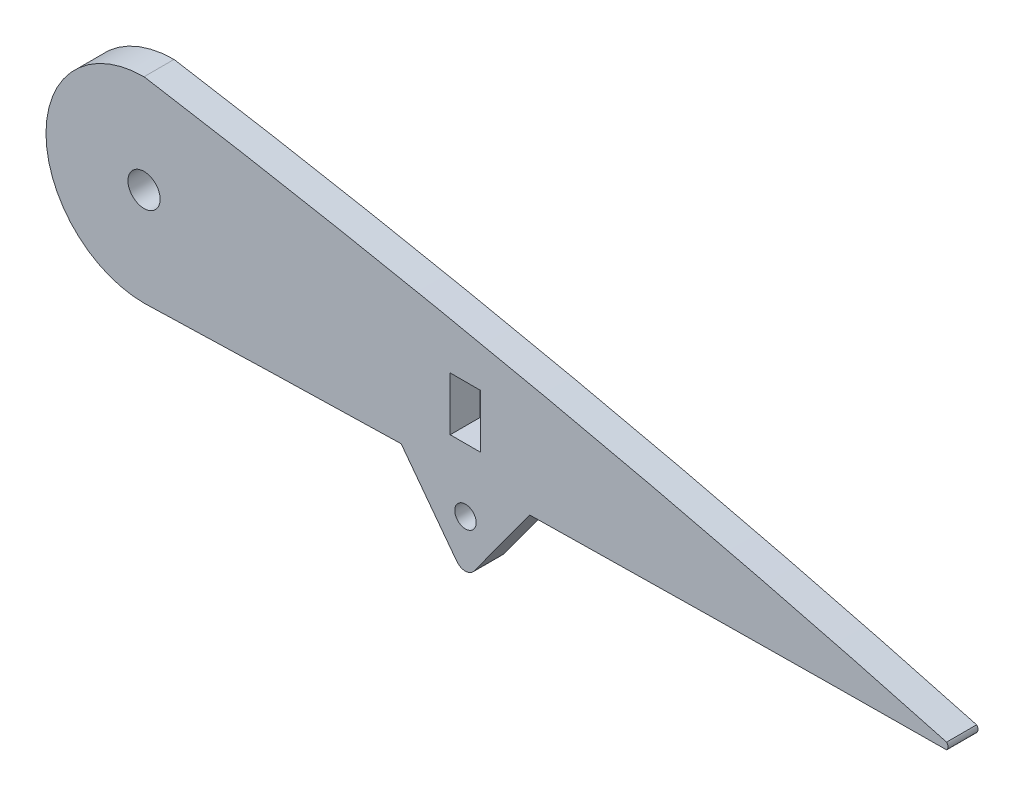
SolidWorks part; units mm, degrees
material "Фанера"
ref_plane "Front Plane" through (0, 0, 0) normal (0, 0, 1) x (1, 0, 0)
ref_plane "Top Plane" through (0, 0, 0) normal (0, 1, 0) x (1, 0, 0)
ref_plane "Right Plane" through (0, 0, 0) normal (1, 0, 0) x (0, 0, -1)
curve "Кривая5"
  spline degree 3 poles (0.048, 0.6214, 0) (0.0227, 0.3735, 0) (-0.0278, -0.1225, 0) (0.078, -0.8844, 0) (0.3497, -1.6388, 0) (0.8143, -2.3651, 0) (1.4635, -3.0393, 0) (2.291, -3.661, 0) (3.3059, -4.2358, 0) (4.5353, -4.7737, 0) (6.0297, -5.2822, 0) (7.869, -5.7653, 0) (10.1688, -6.2217, 0) (13.0754, -6.6396, 0) (16.7281, -6.993, 0) (21.19, -7.2473, 0) (26.4, -7.3766, 0) (32.1974, -7.3763, 0) (38.3978, -7.2614, 0) (44.8576, -7.0566, 0) (51.4865, -6.7865, 0) (58.231, -6.4723, 0) (65.0521, -6.1329, 0) (71.9108, -5.784, 0) (78.7714, -5.4397, 0) (85.6105, -5.111, 0) (92.4321, -4.805, 0) (99.255, -4.532, 0) (106.0974, -4.2783, 0) (112.9692, -4.0031, 0) (119.8644, -3.7232, 0) (126.7739, -3.4401, 0) (133.6816, -3.1587, 0) (140.5819, -2.8824, 0) (147.472, -2.6139, 0) (154.3526, -2.3556, 0) (161.225, -2.1094, 0) (168.0909, -1.8766, 0) (174.9516, -1.6586, 0) (181.8086, -1.4564, 0) (188.6632, -1.2704, 0) (195.5166, -1.1011, 0) (202.3695, -0.9486, 0) (209.2212, -0.8129, 0) (216.0668, -0.6936, 0) (222.8864, -0.5903, 0) (229.6176, -0.5029, 0) (236.0874, -0.4315, 0) (241.9808, -0.3765, 0) (246.559, -0.3395, 0) (249.1205, -0.3213, 0) (250, -0.315, 0) knots 0 0 0 0 0.002941 0.005884 0.009016 0.012365 0.016008 0.020037 0.024574 0.029784 0.035897 0.04324 0.052276 0.063635 0.077983 0.095698 0.11652 0.139661 0.164312 0.189919 0.216157 0.242838 0.269834 0.296993 0.324123 0.351139 0.378036 0.404946 0.431961 0.459078 0.486347 0.513641 0.540929 0.568176 0.59538 0.622543 0.649673 0.676775 0.703855 0.730919 0.757971 0.785018 0.812062 0.839103 0.866132 0.893099 0.919831 0.94581 0.969681 0.98959 1 1 1 1
curve "Кривая6"
  spline degree 3 poles (250, 0.315, 0) (249.1557, 0.545, 0) (246.7202, 1.2085, 0) (242.3913, 2.3583, 0) (236.8498, 3.7876, 0) (230.7799, 5.298, 0) (224.4559, 6.8129, 0) (218.0305, 8.2916, 0) (211.5624, 9.7197, 0) (205.0724, 11.0924, 0) (198.568, 12.4079, 0) (192.0524, 13.6653, 0) (185.5276, 14.8641, 0) (178.9953, 16.0034, 0) (172.4571, 17.0824, 0) (165.9143, 18.0998, 0) (159.3687, 19.0545, 0) (152.8218, 19.9449, 0) (146.2754, 20.7693, 0) (139.7314, 21.5257, 0) (133.1918, 22.212, 0) (126.6587, 22.8257, 0) (120.1368, 23.364, 0) (113.6286, 23.8247, 0) (107.1527, 24.2002, 0) (100.7411, 24.4984, 0) (94.4118, 24.6866, 0) (88.1559, 24.7401, 0) (81.949, 24.6588, 0) (75.7805, 24.441, 0) (69.6537, 24.0819, 0) (63.5754, 23.578, 0) (57.5552, 22.9249, 0) (51.6058, 22.1191, 0) (45.7444, 21.1566, 0) (39.9959, 20.0354, 0) (34.3979, 18.7563, 0) (29.0104, 17.3276, 0) (23.9258, 15.7719, 0) (19.2707, 14.1343, 0) (15.1791, 12.4833, 0) (11.7405, 10.8956, 0) (8.9594, 9.4296, 0) (6.7609, 8.1086, 0) (5.0337, 6.9246, 0) (3.6717, 5.8542, 0) (2.5921, 4.8713, 0) (1.7382, 3.9526, 0) (1.0699, 3.0809, 0) (0.5716, 2.2416, 0) (0.2158, 1.4308, 0) (0.1023, 0.8832, 0) (0.048, 0.6214, 0) knots 0 0 0 0 0.010162 0.029313 0.052012 0.076619 0.101948 0.127526 0.153184 0.178868 0.204558 0.230246 0.255926 0.281594 0.307246 0.332878 0.358485 0.384061 0.409603 0.435104 0.460559 0.485959 0.511303 0.536552 0.561723 0.586629 0.611085 0.635251 0.659272 0.683164 0.706922 0.730536 0.753983 0.777235 0.800246 0.822951 0.845237 0.866916 0.887662 0.906968 0.924203 0.938879 0.950932 0.960693 0.968647 0.975233 0.980795 0.985584 0.989782 0.993521 0.996902 1 1 1 1
sketch "Эскиз1" plane through (0, 0, 0) normal (0, 0, 1) x (1, 0, 0)
  line L0 (250.1305, 0) -> (250.1305, 54.8427) construction
  line L1 (0, 0) -> (0, 70.5199) construction
  line L2 (0, 0) -> (253.0634, 0) construction
  line L3 (62.5326, 62.6361) -> (62.5326, -41.5636) construction
  line L4 (142.5326, 67.9319) -> (142.5326, -57.0034) construction
  line L5 (175.0913, 63.8571) -> (175.0913, -32.3947) construction
  line L6 (32.5326, -14.3434) -> (32.5326, 29.5903) construction
  line L7 (165.9405, 18.0854) -> (165.9405, -1.9504)
  line L8 (199.0913, -1.0223) -> (204.28, -7.9265)
  line L9 (203.6663, 6.9939) -> (206.5163, 6.9939)
  line L10 (203.6663, 6.9939) -> (203.6663, 1.9939)
  line L11 (203.6663, 1.9939) -> (206.5163, 1.9939)
  line L12 (206.5163, 6.9939) -> (206.5163, 1.9939)
  line L13 (203.6663, 6.9939) -> (206.5163, 1.9939) construction
  line L14 (203.6663, 1.9939) -> (206.5163, 6.9939) construction
  line L15 (205.8873, -7.915) -> (211.0913, -0.7814)
  line L16 (205.0913, 14.1754) -> (205.0913, -11.6971) construction
  arc A0 (250, 0.315) -> (250, -0.315) centre (249.685, 0) cw
  circle A1 centre (62.5326, 8.5962) radius 8.1
  circle A2 centre (142.5326, 8.5962) radius 5.1
  circle A3 centre (32.5326, 5.4481) radius 7
  circle A5 centre (102.5326, 8.5962) radius 9.5
  arc A6 (175.0913, -1.657) -> (175.0913, 16.6448) centre (175.0913, 7.4939) cw
  circle A7 centre (175.0913, 7.4939) radius 1.5
  arc A8 (204.28, -7.9265) -> (205.8873, -7.915) centre (205.0794, -7.3257) ccw
  circle A9 centre (205.0913, -3.9061) radius 1
  spline S0 degree 3 poles (0.048, 0.6214) (0.0227, 0.3735) (-0.0278, -0.1225) (0.078, -0.8844) (0.3497, -1.6388) (0.8143, -2.3651) (1.4635, -3.0393) (2.291, -3.661) (3.3059, -4.2358) (4.5353, -4.7737) (6.0297, -5.2822) (7.869, -5.7653) (10.1688, -6.2217) (13.0754, -6.6396) (16.7281, -6.993) (21.19, -7.2473) (26.4, -7.3766) (32.1974, -7.3763) (38.3978, -7.2614) (44.8576, -7.0566) (51.4865, -6.7865) (58.231, -6.4723) (65.0521, -6.1329) (71.9108, -5.784) (78.7714, -5.4397) (85.6105, -5.111) (92.4321, -4.805) (99.255, -4.532) (106.0974, -4.2783) (112.9692, -4.0031) (119.8644, -3.7232) (126.7739, -3.4401) (133.6816, -3.1587) (140.5819, -2.8824) (147.472, -2.6139) (154.3526, -2.3556) (161.225, -2.1094) (168.0909, -1.8766) (174.9516, -1.6586) (181.8086, -1.4564) (188.6632, -1.2704) (195.5166, -1.1011) (202.3695, -0.9486) (211.4992, -0.7677) (220.6031, -0.6199) (229.6176, -0.5029) (236.0874, -0.4315) (241.9808, -0.3765) (246.559, -0.3395) (249.1205, -0.3213) (250, -0.315) knots 0 0 0 0 0.002941 0.005884 0.009016 0.012365 0.016008 0.020037 0.024574 0.029784 0.035897 0.04324 0.052276 0.063635 0.077983 0.095698 0.11652 0.139661 0.164312 0.189919 0.216157 0.242838 0.269834 0.296993 0.324123 0.351139 0.378036 0.404946 0.431961 0.459078 0.486347 0.513641 0.540929 0.568176 0.59538 0.622543 0.649673 0.676775 0.703855 0.730919 0.757971 0.785018 0.812062 0.839103 0.893099 0.919831 0.94581 0.969681 0.98959 1 1 1 1 construction
  spline S1 degree 3 poles (1320.2398, 2793.1983) (437.644, -77.4861) (344.4946, -24.7622) (242.3913, 2.3583) (236.8498, 3.7876) (230.7799, 5.298) (224.4559, 6.8129) (218.0305, 8.2916) (211.5624, 9.7197) (205.0724, 11.0924) (198.568, 12.4079) (192.0524, 13.6653) (185.5276, 14.8641) (178.9953, 16.0034) (172.4571, 17.0824) (165.9143, 18.0998) (159.3687, 19.0545) (152.8218, 19.9449) (146.2754, 20.7693) (139.7314, 21.5257) (133.1918, 22.212) (126.6587, 22.8257) (120.1368, 23.364) (113.6286, 23.8247) (107.1527, 24.2002) (100.7411, 24.4984) (94.4118, 24.6866) (88.1559, 24.7401) (81.949, 24.6588) (75.7805, 24.441) (69.6537, 24.0819) (63.5754, 23.578) (57.5552, 22.9249) (51.6058, 22.1191) (45.7444, 21.1566) (39.9959, 20.0354) (34.3979, 18.7563) (29.0104, 17.3276) (23.9258, 15.7719) (19.2707, 14.1343) (15.1791, 12.4833) (11.7405, 10.8956) (8.9594, 9.4296) (6.7609, 8.1086) (5.0337, 6.9246) (3.6717, 5.8542) (2.5921, 4.8713) (1.7382, 3.9526) (1.0699, 3.0809) (0.5716, 2.2416) (-4.988, -10.4257) (54.4994, -42.1703) (-2884.0898, 821.1456) knots -1.174773 -1.174773 -1.174773 -1.174773 0.010162 0.029313 0.052012 0.076619 0.101948 0.127526 0.153184 0.178868 0.204558 0.230246 0.255926 0.281594 0.307246 0.332878 0.358485 0.384061 0.409603 0.435104 0.460559 0.485959 0.511303 0.536552 0.561723 0.586629 0.611085 0.635251 0.659272 0.683164 0.706922 0.730536 0.753983 0.777235 0.800246 0.822951 0.845237 0.866916 0.887662 0.906968 0.924203 0.938879 0.950932 0.960693 0.968647 0.975233 0.980795 0.985584 0.989782 0.993521 0.996902 1.14942 1.14942 1.14942 1.14942 only from (250, 0.315) to (0.048, 0.6214) construction
  spline S2 degree 3 poles (0.048, 0.6214) (0.0227, 0.3735) (-0.0278, -0.1225) (0.078, -0.8844) (0.3497, -1.6388) (0.8143, -2.3651) (1.4635, -3.0393) (2.291, -3.661) (3.3059, -4.2358) (4.5353, -4.7737) (6.0297, -5.2822) (7.869, -5.7653) (10.1688, -6.2217) (13.0754, -6.6396) (16.7281, -6.993) (21.19, -7.2473) (26.4, -7.3766) (32.1974, -7.3763) (38.3978, -7.2614) (44.8576, -7.0566) (51.4865, -6.7865) (58.231, -6.4723) (65.0521, -6.1329) (71.9108, -5.784) (78.7714, -5.4397) (85.6105, -5.111) (92.4321, -4.805) (99.255, -4.532) (106.0974, -4.2783) (112.9692, -4.0031) (119.8644, -3.7232) (126.7739, -3.4401) (133.6816, -3.1587) (140.5819, -2.8824) (147.472, -2.6139) (154.3526, -2.3556) (161.225, -2.1094) (168.0909, -1.8766) (174.9516, -1.6586) (181.8086, -1.4564) (188.6632, -1.2704) (194.4239, -1.1281) (197.8998, -1.0487) (199.0913, -1.0223) knots 0 0 0 0 0.002941 0.005884 0.009016 0.012365 0.016008 0.020037 0.024574 0.029784 0.035897 0.04324 0.052276 0.063635 0.077983 0.095698 0.11652 0.139661 0.164312 0.189919 0.216157 0.242838 0.269834 0.296993 0.324123 0.351139 0.378036 0.404946 0.431961 0.459078 0.486347 0.513641 0.540929 0.568176 0.59538 0.622543 0.649673 0.676775 0.703855 0.730919 0.757971 0.785018 0.799124 0.799124 0.799124 0.799124
  spline S3 degree 3 poles (250, 0.315) (249.1557, 0.545) (246.7202, 1.2085) (242.3913, 2.3583) (236.8498, 3.7876) (230.7799, 5.298) (224.4559, 6.8129) (218.0305, 8.2916) (211.5624, 9.7197) (205.0724, 11.0924) (198.568, 12.4079) (192.0524, 13.6653) (185.5276, 14.8641) (178.9953, 16.0034) (172.4571, 17.0824) (165.9143, 18.0998) (159.3687, 19.0545) (152.8218, 19.9449) (146.2754, 20.7693) (139.7314, 21.5257) (133.1918, 22.212) (126.6587, 22.8257) (120.1368, 23.364) (113.6286, 23.8247) (107.1527, 24.2002) (100.7411, 24.4984) (94.4118, 24.6866) (88.1559, 24.7401) (81.949, 24.6588) (75.7805, 24.441) (69.6537, 24.0819) (63.5754, 23.578) (57.5552, 22.9249) (51.6058, 22.1191) (45.7444, 21.1566) (39.9959, 20.0354) (34.3979, 18.7563) (29.0104, 17.3276) (23.9258, 15.7719) (19.2707, 14.1343) (15.1791, 12.4833) (11.7405, 10.8956) (8.9594, 9.4296) (6.7609, 8.1086) (5.0337, 6.9246) (3.6717, 5.8542) (2.5921, 4.8713) (1.7382, 3.9526) (1.0699, 3.0809) (0.5716, 2.2416) (0.2158, 1.4308) (0.1023, 0.8832) (0.048, 0.6214) knots 0 0 0 0 0.010162 0.029313 0.052012 0.076619 0.101948 0.127526 0.153184 0.178868 0.204558 0.230246 0.255926 0.281594 0.307246 0.332878 0.358485 0.384061 0.409603 0.435104 0.460559 0.485959 0.511303 0.536552 0.561723 0.586629 0.611085 0.635251 0.659272 0.683164 0.706922 0.730536 0.753983 0.777235 0.800246 0.822951 0.845237 0.866916 0.887662 0.906968 0.924203 0.938879 0.950932 0.960693 0.968647 0.975233 0.980795 0.985584 0.989782 0.993521 0.996902 1 1 1 1
  spline S4 degree 3 poles (211.0913, -0.7814) (215.0296, -0.7106) (221.2261, -0.6119) (229.6176, -0.5029) (236.0874, -0.4315) (241.9808, -0.3765) (246.559, -0.3395) (249.1205, -0.3213) (250, -0.315) knots 0.846478 0.846478 0.846478 0.846478 0.893099 0.919831 0.94581 0.969681 0.98959 1 1 1 1
  point P22 (62.5326, 23.4501)
  point P23 (62.5326, -6.2577)
  point P26 (32.5326, 18.2506)
  point P27 (32.5326, -7.3543)
  point P30 (175.0913, 16.6448)
  point P31 (175.0913, -1.657)
  point P37 (205.0913, 4.4939)
  point P48 (0, 0)
  point P51 (205.0913, -9.0061)
  dimension "D3" = 16.2
  dimension "D8" = 14
  dimension "D10" = 10.2
  dimension "D9" = 19
  dimension "D15" = 9.1509
  dimension "D16" = 3
  dimension "D24" = 1
  dimension "D25" = 2
  dimension "D1" = 250.1305
  dimension "D2" = 62.5326
  dimension "D4" = 80
  dimension "D5" = 75.0391
  dimension "D6" = 29.7079
  dimension "D7" = 14.8539
  dimension "D11" = 40
  dimension "D12" = 30
  dimension "D13" = 25.6049
  dimension "D14" = 12.8025
  dimension "D17" = 2.85
  dimension "D18" = 5
  dimension "D19" = 30
  dimension "D20" = 3
  dimension "D21" = 6
  dimension "D22" = 6
  dimension "D23" = 13.5
  dimension "D26" = 8.4
extrude "Бобышка-Вытянуть1" add sketch "Эскиз1" along normal mid plane 2.8 contours A0 S3 A6 S2 A7
equation "\"D2@Эскиз1\"=\"D1@Эскиз1\"/4"
equation "\"D7@Эскиз1\"=\"D6@Эскиз1\"/2"
equation "\"D5@Эскиз1\"=\"D1@Эскиз1\"*0.3"
equation "\"D14@Эскиз1\"=\"D13@Эскиз1\"/2"
equation "\"t\"= 2.85"
